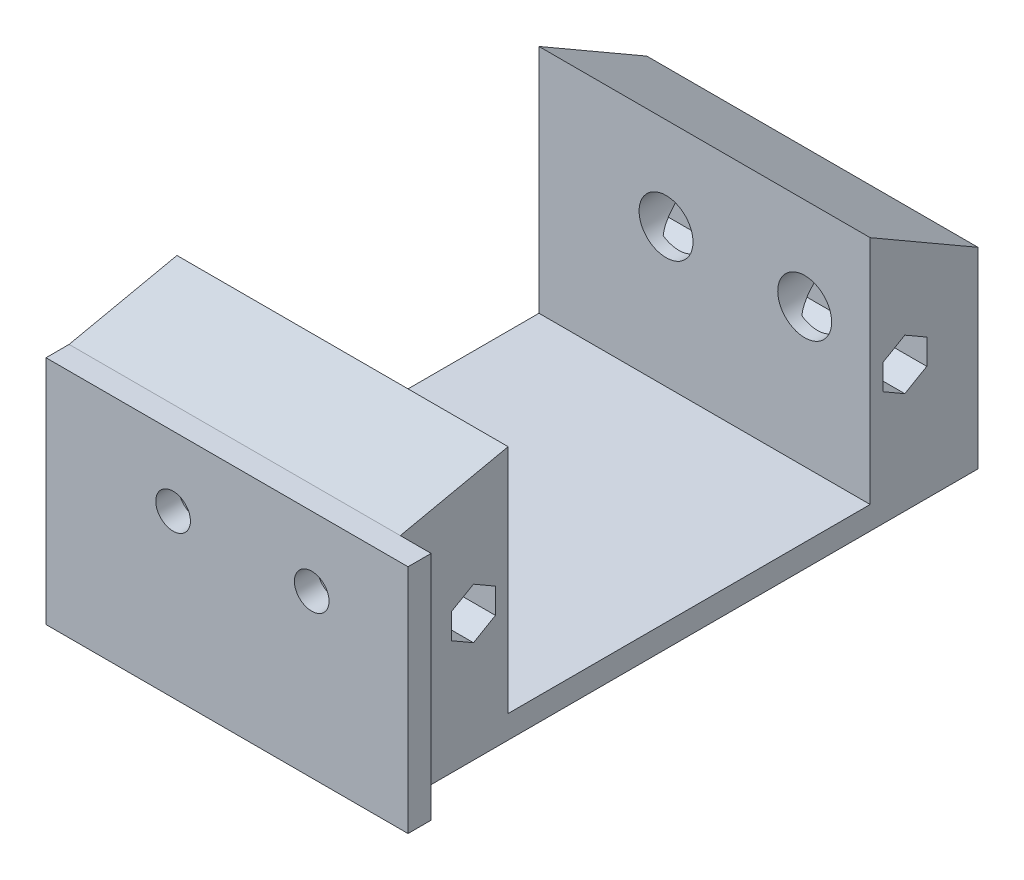
SolidWorks part; units mm, degrees
ref_plane "Front Plane" through (0, 0, 0) normal (0, 0, 1) x (1, 0, 0)
ref_plane "Top Plane" through (0, 0, 0) normal (0, 1, 0) x (1, 0, 0)
ref_plane "Right Plane" through (0, 0, 0) normal (1, 0, 0) x (0, 0, -1)
sketch "Sketch1" plane through (0, 0, 0) normal (0, 0, 1) x (1, 0, 0)
  line L0 (0, 0) -> (47, 0)
  line L1 (47, 0) -> (47, 30)
  line L2 (47, 30) -> (0, 30)
  line L3 (0, 30) -> (0, 0)
  line L4 (47, 15) -> (24.4455, 15) construction
  circle A0 centre (16.5, 21) radius 2.25
  circle A1 centre (34.5, 21) radius 2.25
  dimension "D6" = 4.5
  dimension "D1" = 47
  dimension "D2" = 30
  dimension "D3" = 18
  dimension "D4" = 6
  dimension "D5" = 12.5
extrude "Boss-Extrude1" add sketch "Sketch1" along normal blind 3
sketch "Sketch2" plane through (0, 0, 0) normal (-1, 0, 0) x (0, 0, 1)
  line L0 (0, 0) -> (-75, 0)
  line L1 (-61, 33) -> (-61, 3)
  line L2 (-14, 33) -> (-14, 3)
  line L3 (-61, 16.3119) -> (-14, 16.3119) construction
  line L4 (-37.5, 0) -> (-37.5, 34.4937) construction
  line L5 (0, 3) -> (-75, 3)
  line L6 (0, 30) -> (0, 0) construction
  line L7 (-75, 3) -> (-75, 0)
  line L8 (-61, 33) -> (-75, 24.9171)
  line L9 (-75, 24.9171) -> (-75, 3)
  line L10 (-14, 33) -> (0, 30)
  line L11 (0, 30) -> (0, 3)
  line L12 (-65.5, 16.5) -> (-9.5, 16.5) construction
  circle A0 centre (-65.5, 16.5) radius 1.9
  circle A1 centre (-9.5, 16.5) radius 1.9
  point P11 (-37.5, 16.3119)
  point P22 (-37.5, 16.5)
  line M9 (0, 30) -> (0, 0)
  dimension "D9" = 3.8
  dimension "D1" = 75
  dimension "D2" = 47
  dimension "D3" = 3
  dimension "D4" = 30
  dimension "D5" = 60
  dimension "D6" = 56
  dimension "D8" = 13.5
extrude "Boss-Extrude2" add sketch "Sketch2" against normal blind 43 contours L8 L9 L5 L1 A0 | L5 L7 L0 M9 | L10 L2 L5 A1 M9
sketch "Sketch3" plane through (0, 0, -75) normal (0, 0, -1) x (-1, 0, 0)
  circle A0 centre (-34.5, 21) radius 3.5
  circle A1 centre (-16.5, 21) radius 3.5
  circle A2 centre (-16.5, 21) radius 2.25 construction
  circle A3 centre (-34.5, 21) radius 2.25 construction
  dimension "D1" = 7
extrude "Cut-Extrude1" cut sketch "Sketch3" against normal up to surface (75 mm away) up to face at (45, 15, 0)
sketch "Sketch4" plane through (43, 0, 0) normal (1, 0, 0) x (0, 0, -1)
  line L1 (9.5, 13.2091) -> (12.35, 14.8546)
  line L2 (12.35, 14.8546) -> (12.35, 18.1454)
  line L3 (12.35, 18.1454) -> (9.5, 19.7909)
  line L4 (9.5, 19.7909) -> (6.65, 18.1454)
  line L5 (6.65, 18.1454) -> (6.65, 14.8546)
  line L6 (6.65, 14.8546) -> (9.5, 13.2091)
  line L7 (65.5, 13.2091) -> (68.35, 14.8546)
  line L8 (68.35, 14.8546) -> (68.35, 18.1454)
  line L9 (68.35, 18.1454) -> (65.5, 19.7909)
  line L10 (65.5, 19.7909) -> (62.65, 18.1454)
  line L11 (62.65, 18.1454) -> (62.65, 14.8546)
  line L12 (62.65, 14.8546) -> (65.5, 13.2091)
  circle A0 centre (9.5, 16.5) radius 2.85 construction
  circle A1 centre (65.5, 16.5) radius 2.85 construction
  circle A2 centre (9.5, 16.5) radius 1.9 construction
  dimension "D1" = 5.7
extrude "Cut-Extrude2" cut sketch "Sketch4" against normal offset from surface (39 mm away) 4 up to face at (0, 17.4352, -32.6667)
